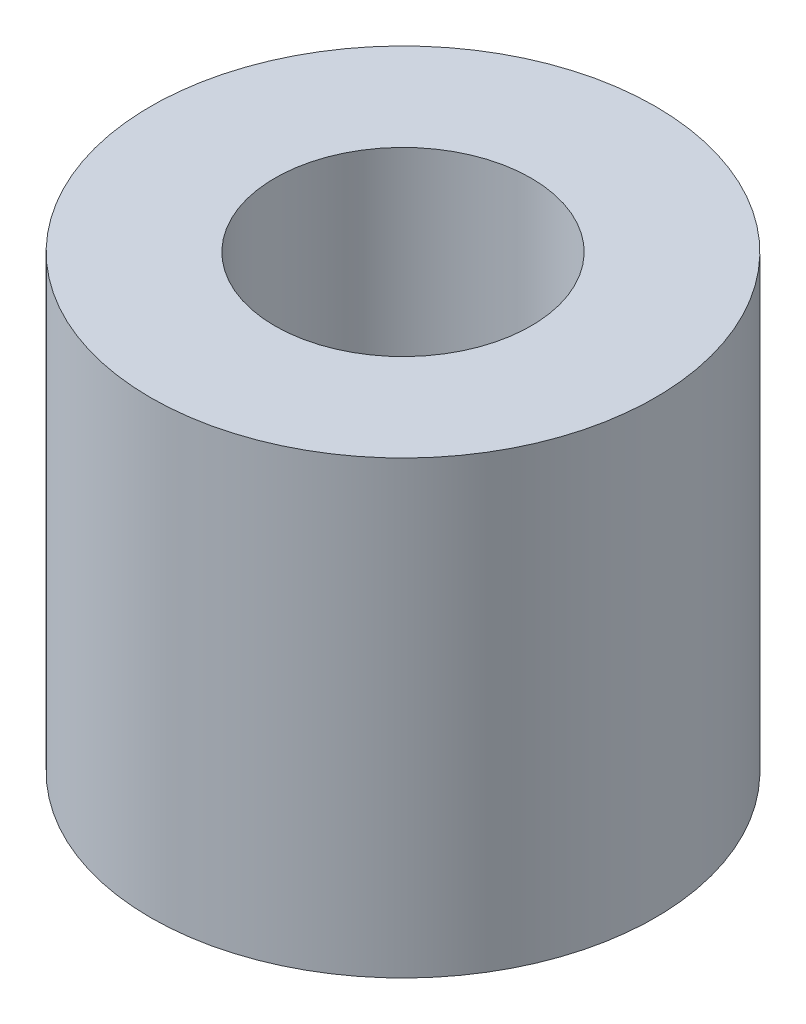
SolidWorks part; units mm, degrees
ref_plane "前视基准面" through (0, 0, 0) normal (0, 0, 1) x (1, 0, 0)
ref_plane "上视基准面" through (0, 0, 0) normal (0, 1, 0) x (1, 0, 0)
ref_plane "右视基准面" through (0, 0, 0) normal (1, 0, 0) x (0, 0, -1)
other "Configuration Table"
sketch "草图1" plane through (0, 0, 0) normal (0, 1, 0) x (1, 0, 0)
  circle A0 centre (0, 0) radius 3.25
  circle A1 centre (0, 0) radius 1.65
  dimension "D1" = 6.5
  dimension "D2" = 3.3
extrude "凸台-拉伸1" add sketch "草图1" along normal blind 5.8
